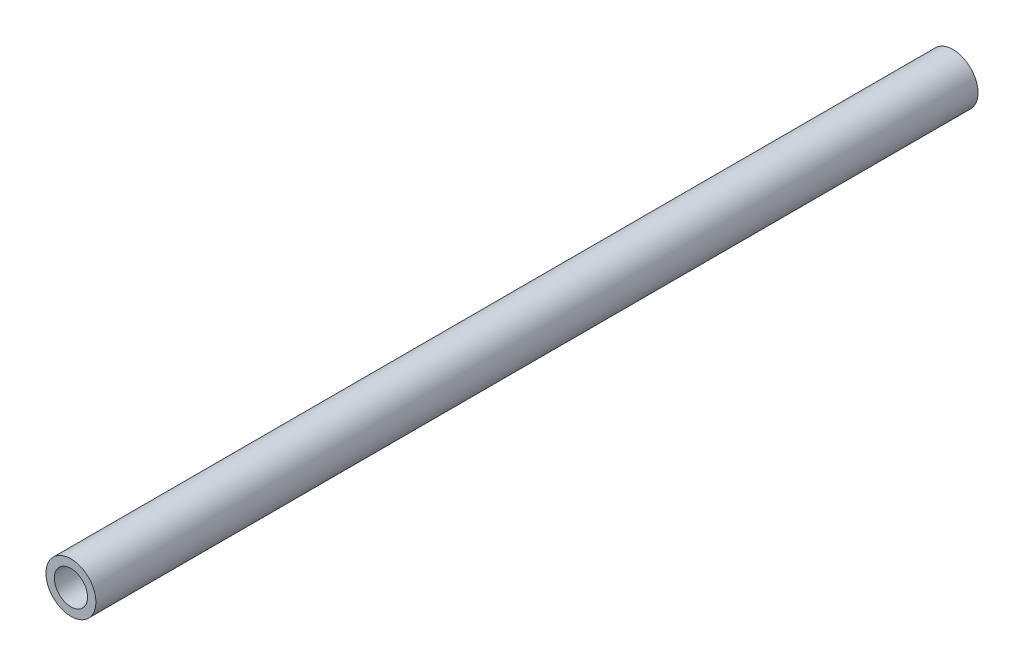
SolidWorks part; units mm, degrees
ref_plane "Front Plane" through (0, 0, 0) normal (0, 0, 1) x (1, 0, 0)
ref_plane "Top Plane" through (0, 0, 0) normal (0, 1, 0) x (1, 0, 0)
ref_plane "Right Plane" through (0, 0, 0) normal (1, 0, 0) x (0, 0, -1)
sketch "Sketch1" plane through (0, 0, 0) normal (0, 0, 1) x (1, 0, 0)
  circle A0 centre (0, 0) radius 5
  circle A1 centre (0, 0) radius 7.5
  dimension "D1" = 10
  dimension "D2" = 15
extrude "Boss-Extrude1" add sketch "Sketch1" along normal blind 265
